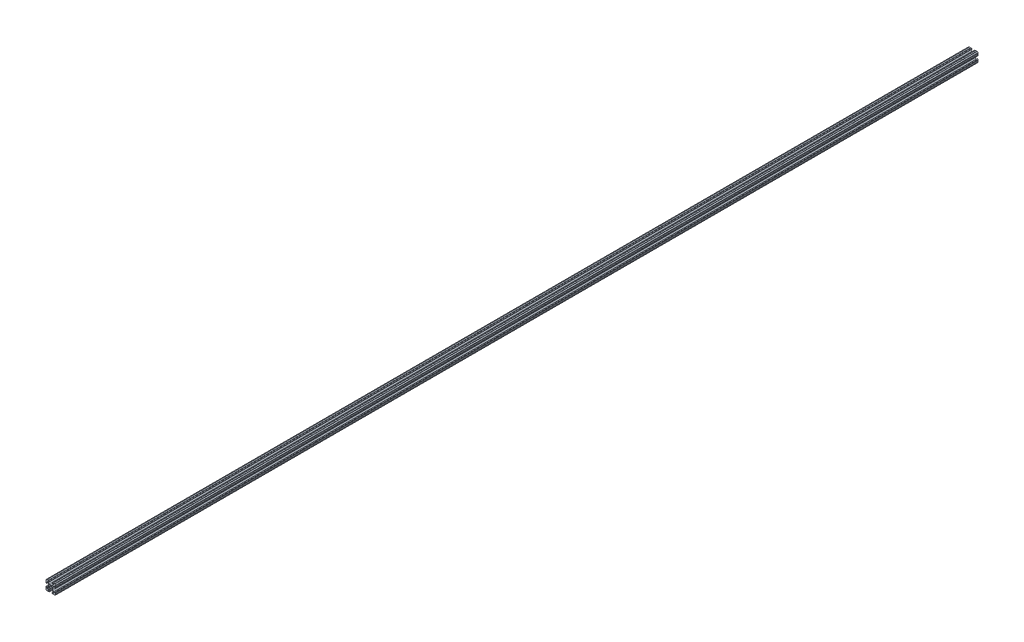
SolidWorks part; units mm, degrees
ref_plane "Front Plane" through (0, 0, 0) normal (0, 0, 1) x (1, 0, 0)
ref_plane "Top Plane" through (0, 0, 0) normal (0, 1, 0) x (1, 0, 0)
ref_plane "Right Plane" through (0, 0, 0) normal (1, 0, 0) x (0, 0, -1)
ref_plane "Plane1" through (0, 0, -101.6) normal (0, 0, -1) x (-1, 0, 0)
sketch "Sketch1" plane through (0, 0, -101.6) normal (0, 0, -1) x (-1, 0, 0)
  line L0 (12.7, -9.5504) -> (12.7, -6.3331)
  line L1 (12.7, -5.3171) -> (12.7, -4.3434)
  line L2 (10.4902, -4.3434) -> (10.4902, -6.4748)
  line L3 (8.7558, -7.1932) -> (5.4257, -3.8632)
  line L4 (4.4958, -1.6181) -> (4.4958, 1.6181)
  line L5 (5.4257, 3.8632) -> (8.7558, 7.1932)
  line L6 (10.4902, 6.4748) -> (10.4902, 4.3434)
  line L7 (12.7, 4.3434) -> (12.7, 5.3171)
  line L8 (12.7, 6.3331) -> (12.7, 9.5504)
  line L9 (9.5504, 12.7) -> (6.3331, 12.7)
  line L10 (5.3171, 12.7) -> (4.3434, 12.7)
  line L11 (4.3434, 10.4902) -> (6.4748, 10.4902)
  line L12 (7.1932, 8.7558) -> (3.8632, 5.4257)
  line L13 (1.6181, 4.4958) -> (-1.6181, 4.4958)
  line L14 (-3.8632, 5.4257) -> (-7.1932, 8.7558)
  line L15 (-6.4748, 10.4902) -> (-4.3434, 10.4902)
  line L16 (-4.3434, 12.7) -> (-5.3171, 12.7)
  line L17 (-6.3331, 12.7) -> (-9.5504, 12.7)
  line L18 (-12.7, 9.5504) -> (-12.7, 6.3331)
  line L19 (-12.7, 5.3171) -> (-12.7, 4.3434)
  line L20 (-10.4902, 4.3434) -> (-10.4902, 6.4748)
  line L21 (-8.7558, 7.1932) -> (-5.4257, 3.8632)
  line L22 (-4.4958, 1.6181) -> (-4.4958, -1.6181)
  line L23 (-5.4257, -3.8632) -> (-8.7558, -7.1932)
  line L24 (-10.4902, -6.4748) -> (-10.4902, -4.3434)
  line L25 (-12.7, -4.3434) -> (-12.7, -5.3171)
  line L26 (-12.7, -6.3331) -> (-12.7, -9.5504)
  line L27 (-9.5504, -12.7) -> (-6.3331, -12.7)
  line L28 (-5.3171, -12.7) -> (-4.3434, -12.7)
  line L29 (-4.3434, -10.4902) -> (-6.4748, -10.4902)
  line L30 (-7.1932, -8.7558) -> (-3.8632, -5.4257)
  line L31 (-1.6181, -4.4958) -> (1.6181, -4.4958)
  line L32 (3.8632, -5.4257) -> (7.1932, -8.7558)
  line L33 (6.4748, -10.4902) -> (4.3434, -10.4902)
  line L34 (4.3434, -12.7) -> (5.3171, -12.7)
  line L35 (6.3331, -12.7) -> (9.5504, -12.7)
  arc A0 (12.6998, -10.5664) -> (12.7, -9.5504) centre (12.7, -10.0584) cw
  arc A1 (12.7, -6.3331) -> (12.7, -5.3171) centre (12.7, -5.8251) cw
  arc A2 (12.7, -4.3434) -> (10.4902, -4.3434) centre (11.5951, -4.3434) ccw
  arc A3 (10.4902, -6.4748) -> (8.7558, -7.1932) centre (9.4742, -6.4748) cw
  arc A4 (5.4257, -3.8632) -> (4.4958, -1.6181) centre (7.6708, -1.6181) cw
  arc A5 (4.4958, 1.6181) -> (5.4257, 3.8632) centre (7.6708, 1.6181) cw
  arc A6 (8.7558, 7.1932) -> (10.4902, 6.4748) centre (9.4742, 6.4748) cw
  arc A7 (10.4902, 4.3434) -> (12.7, 4.3434) centre (11.5951, 4.3434) ccw
  arc A8 (12.7, 5.3171) -> (12.7, 6.3331) centre (12.7, 5.8251) cw
  arc A9 (12.7, 9.5504) -> (12.6998, 10.5664) centre (12.7, 10.0584) cw
  arc A10 (12.6998, 10.5664) -> (10.5664, 12.6998) centre (10.5918, 10.5918) ccw
  arc A11 (10.5664, 12.6998) -> (9.5504, 12.7) centre (10.0584, 12.7) cw
  arc A12 (6.3331, 12.7) -> (5.3171, 12.7) centre (5.8251, 12.7) cw
  arc A13 (4.3434, 12.7) -> (4.3434, 10.4902) centre (4.3434, 11.5951) ccw
  arc A14 (6.4748, 10.4902) -> (7.1932, 8.7558) centre (6.4748, 9.4742) cw
  arc A15 (3.8632, 5.4257) -> (1.6181, 4.4958) centre (1.6181, 7.6708) cw
  arc A16 (-1.6181, 4.4958) -> (-3.8632, 5.4257) centre (-1.6181, 7.6708) cw
  arc A17 (-7.1932, 8.7558) -> (-6.4748, 10.4902) centre (-6.4748, 9.4742) cw
  arc A18 (-4.3434, 10.4902) -> (-4.3434, 12.7) centre (-4.3434, 11.5951) ccw
  arc A19 (-5.3171, 12.7) -> (-6.3331, 12.7) centre (-5.8251, 12.7) cw
  arc A20 (-9.5504, 12.7) -> (-10.5664, 12.6998) centre (-10.0584, 12.7) cw
  arc A21 (-10.5664, 12.6998) -> (-12.6998, 10.5664) centre (-10.5918, 10.5918) ccw
  arc A22 (-12.6998, 10.5664) -> (-12.7, 9.5504) centre (-12.7, 10.0584) cw
  arc A23 (-12.7, 6.3331) -> (-12.7, 5.3171) centre (-12.7, 5.8251) cw
  arc A24 (-12.7, 4.3434) -> (-10.4902, 4.3434) centre (-11.5951, 4.3434) ccw
  arc A25 (-10.4902, 6.4748) -> (-8.7558, 7.1932) centre (-9.4742, 6.4748) cw
  arc A26 (-5.4257, 3.8632) -> (-4.4958, 1.6181) centre (-7.6708, 1.6181) cw
  arc A27 (-4.4958, -1.6181) -> (-5.4257, -3.8632) centre (-7.6708, -1.6181) cw
  arc A28 (-8.7558, -7.1932) -> (-10.4902, -6.4748) centre (-9.4742, -6.4748) cw
  arc A29 (-10.4902, -4.3434) -> (-12.7, -4.3434) centre (-11.5951, -4.3434) ccw
  arc A30 (-12.7, -5.3171) -> (-12.7, -6.3331) centre (-12.7, -5.8251) cw
  arc A31 (-12.7, -9.5504) -> (-12.6998, -10.5664) centre (-12.7, -10.0584) cw
  arc A32 (-12.6998, -10.5664) -> (-10.5664, -12.6998) centre (-10.5918, -10.5918) ccw
  arc A33 (-10.5664, -12.6998) -> (-9.5504, -12.7) centre (-10.0584, -12.7) cw
  arc A34 (-6.3331, -12.7) -> (-5.3171, -12.7) centre (-5.8251, -12.7) cw
  arc A35 (-4.3434, -12.7) -> (-4.3434, -10.4902) centre (-4.3434, -11.5951) ccw
  arc A36 (-6.4748, -10.4902) -> (-7.1932, -8.7558) centre (-6.4748, -9.4742) cw
  arc A37 (-3.8632, -5.4257) -> (-1.6181, -4.4958) centre (-1.6181, -7.6708) cw
  arc A38 (1.6181, -4.4958) -> (3.8632, -5.4257) centre (1.6181, -7.6708) cw
  arc A39 (7.1932, -8.7558) -> (6.4748, -10.4902) centre (6.4748, -9.4742) cw
  arc A40 (4.3434, -10.4902) -> (4.3434, -12.7) centre (4.3434, -11.5951) ccw
  arc A41 (5.3171, -12.7) -> (6.3331, -12.7) centre (5.8251, -12.7) cw
  arc A42 (9.5504, -12.7) -> (10.5664, -12.6998) centre (10.0584, -12.7) cw
  arc A43 (10.5664, -12.6998) -> (12.6998, -10.5664) centre (10.5918, -10.5918) ccw
  circle A44 centre (0, 0) radius 2.6035
extrude "Boss-Extrude1" add sketch "Sketch1" against normal blind 2438.4
